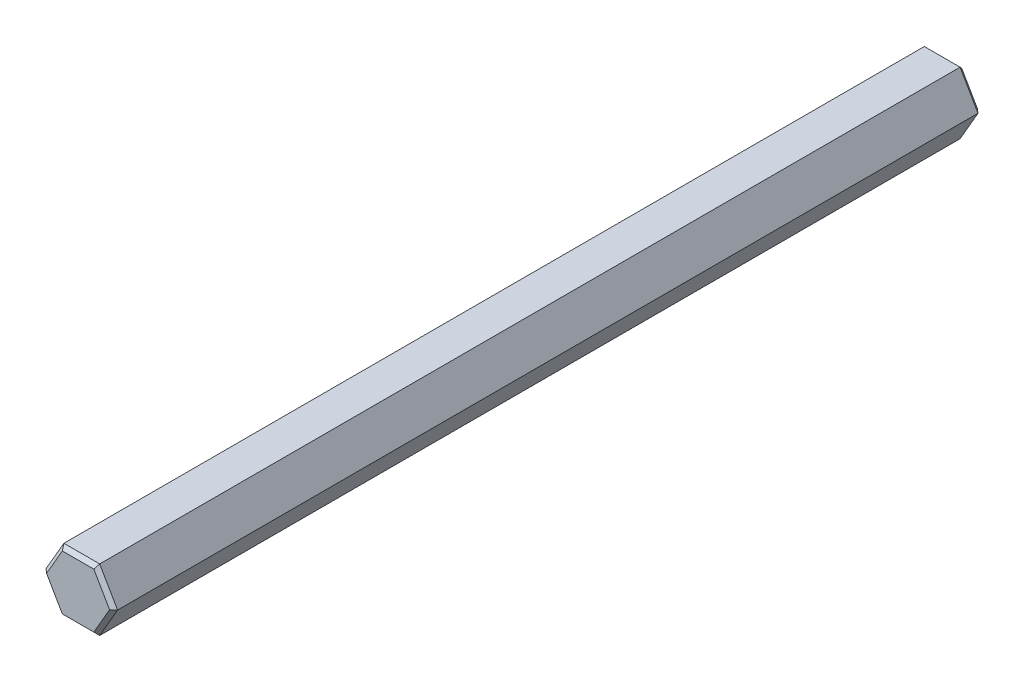
SolidWorks part; units mm, degrees
ref_plane "Front Plane" through (0, 0, 0) normal (0, 0, 1) x (1, 0, 0)
ref_plane "Top Plane" through (0, 0, 0) normal (0, 1, 0) x (1, 0, 0)
ref_plane "Right Plane" through (0, 0, 0) normal (1, 0, 0) x (0, 0, -1)
ref_plane "Plane1" through (0, 0, 0) normal (0, 0, -1) x (-1, 0, 0)
sketch "Sketch1" plane through (0, 0, 0) normal (0, 0, -1) x (-1, 0, 0)
  line L0 (7.3323, 0) -> (3.6662, 6.35)
  line L1 (3.6662, 6.35) -> (-3.6662, 6.35)
  line L2 (-3.6662, 6.35) -> (-7.3323, 0)
  line L3 (-7.3323, 0) -> (-3.6662, -6.35)
  line L4 (-3.6662, -6.35) -> (3.6662, -6.35)
  line L5 (3.6662, -6.35) -> (7.3323, 0)
extrude "Boss-Extrude1" add sketch "Sketch1" against normal blind 177.8
chamfer "Chamfer1" distance 0.762 angle 45 12 edges at (0, -6.35, 177.8) (5.4993, -3.175, 177.8) (-5.4993, -3.175, 177.8) (5.4993, 3.175, 177.8) (-5.4993, 3.175, 177.8) (0, 6.35, 177.8) (5.4993, -3.175, 0) (5.4993, 3.175, 0) (0, -6.35, 0) (0, 6.35, 0) (-5.4993, -3.175, 0) (-5.4993, 3.175, 0)
